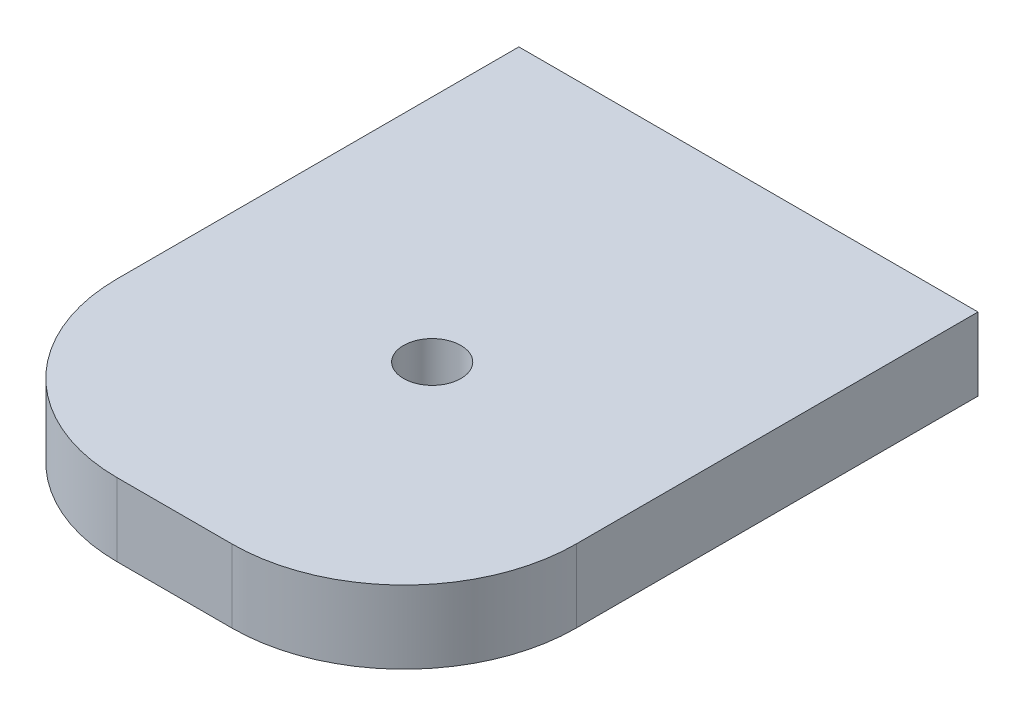
SolidWorks part; units mm, degrees
ref_plane "Front Plane" through (0, 0, 0) normal (0, 0, 1) x (1, 0, 0)
ref_plane "Top Plane" through (0, 0, 0) normal (0, 1, 0) x (1, 0, 0)
ref_plane "Right Plane" through (0, 0, 0) normal (1, 0, 0) x (0, 0, -1)
sketch "Sketch1" plane through (0, 0, 0) normal (0, 1, 0) x (1, 0, 0)
  line L1 (-18.677, 25.214) -> (21.323, 25.214)
  line L2 (-18.677, 25.214) -> (-18.677, -24.786)
  line L3 (-18.677, -24.786) -> (21.323, -24.786)
  line L4 (21.323, 25.214) -> (21.323, -24.786)
  circle A0 centre (1.323, -2.3346) radius 2.5
  dimension "D3" = 5
  dimension "D1" = 40
  dimension "D2" = 50
extrude "Boss-Extrude1" add sketch "Sketch1" along normal blind 6.35
fillet "Fillet1" radius 15 2 edges at (21.323, 3.175, 24.786) (-18.677, 3.175, 24.786)
